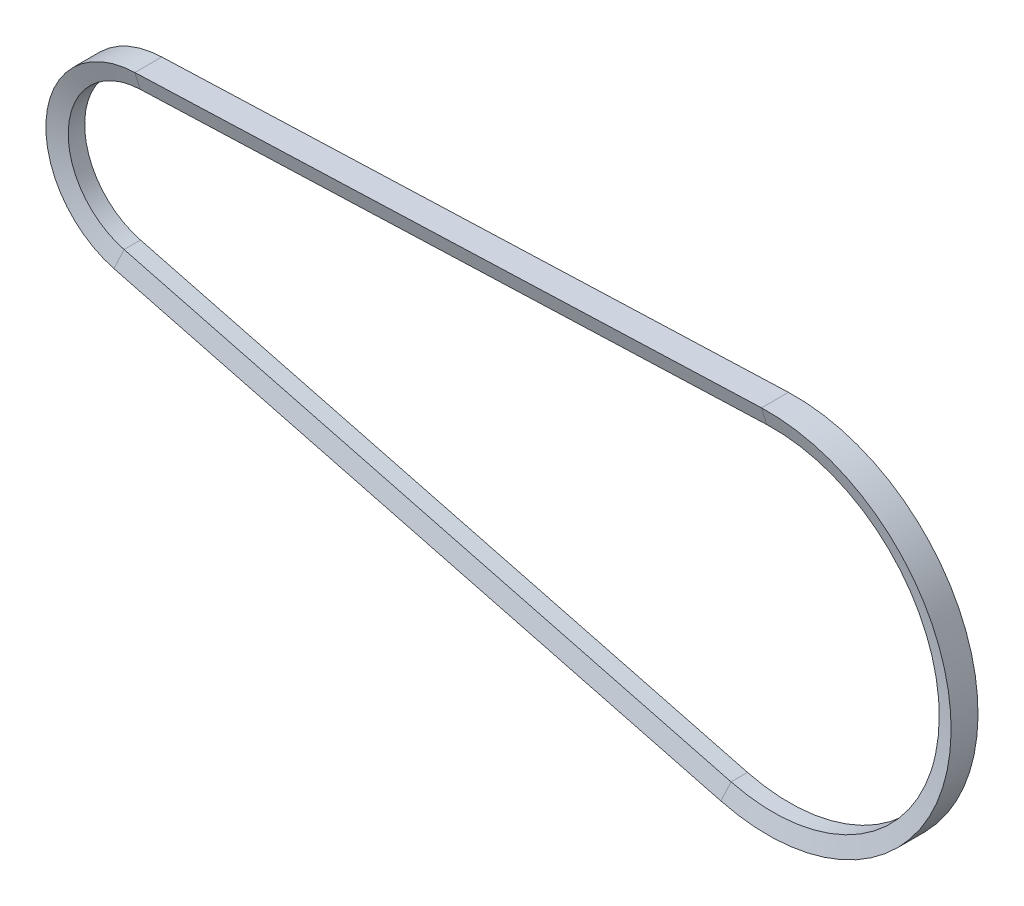
SolidWorks part; units mm, degrees
ref_plane "Front Plane" through (0, 0, 0) normal (0, 0, 1) x (1, 0, 0)
ref_plane "Top Plane" through (0, 0, 0) normal (0, 1, 0) x (1, 0, 0)
ref_plane "Right Plane" through (0, 0, 0) normal (1, 0, 0) x (0, 0, -1)
sketch "Sketch2" plane through (0, 0, 0) normal (0, 0, 1) x (1, 0, 0)
  line L0 (0, 0) -> (1, 0) construction
  line L1 (0, 0) -> (0, 1) construction
  line L2 (-34.1671, -131.6382) -> (-530.384, -2.8436)
  line L3 (-517.29, 117.1592) -> (-4.974, 135.909)
  arc A0 (-4.974, 135.909) -> (-34.1671, -131.6382) centre (0, 0) cw
  arc A1 (-530.384, -2.8436) -> (-517.29, 117.1592) centre (-515.059, 56.2) cw
ref_plane "Plane1" through (-4.974, 0, 0) normal (1, 0, 0) x (0, 0, -1)
sketch "Sketch3" plane through (-4.974, 0, 0) normal (1, 0, 0) x (0, 0, -1)
  line L0 (-7.572, 135.909) -> (5.868, 135.909)
  line L2 (5.868, 135.909) -> (10.148, 149.9083)
  line L3 (10.148, 149.9083) -> (-11.852, 149.9083)
  line L4 (-11.852, 149.9083) -> (-7.572, 135.909)
  point P3 (-0.852, 135.909)
  dimension "D1" = 13.44
  dimension "D2" = 22
  dimension "D3" = 73
  dimension "D4" = 73
sweep "Sweep1" add profiles "Sketch3" path "Sketch2"
